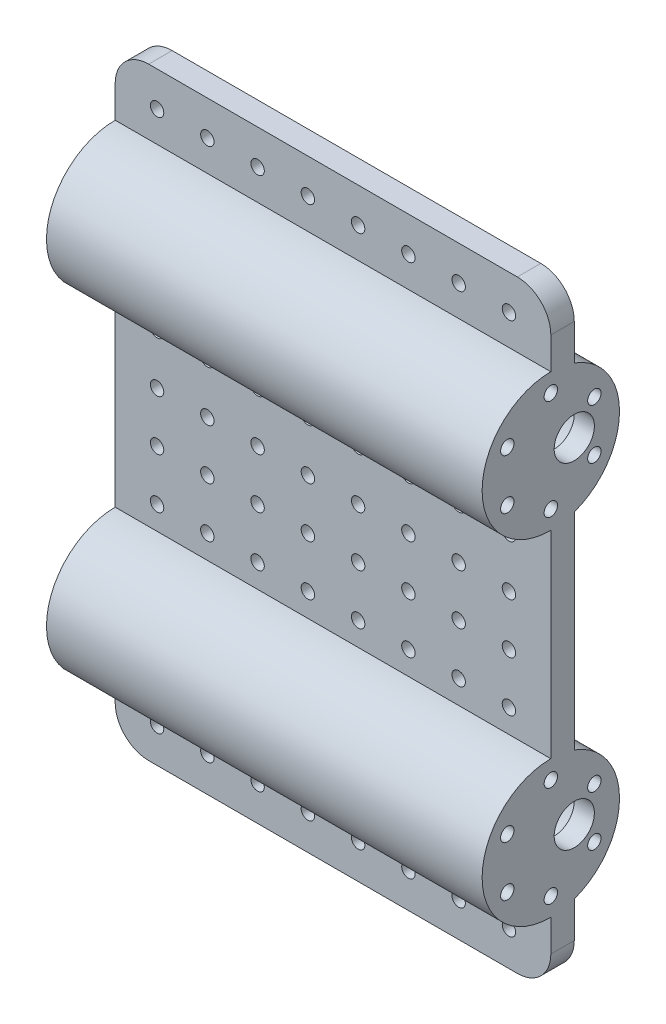
SolidWorks part; units mm, degrees
ref_plane "Ebene vorne" through (0, 0, 0) normal (0, 0, 1) x (1, 0, 0)
ref_plane "Ebene oben" through (0, 0, 0) normal (0, 1, 0) x (1, 0, 0)
ref_plane "Ebene rechts" through (0, 0, 0) normal (1, 0, 0) x (0, 0, -1)
sketch "Skizze1" plane through (0, 0, 0) normal (0, 0, 1) x (1, 0, 0)
  line L1 (0, 0) -> (130, 0)
  line L2 (0, 0) -> (0, 180)
  line L3 (0, 180) -> (130, 180)
  line L4 (130, 0) -> (130, 180)
  dimension "D1" = 130
  dimension "D2" = 180
extrude "Aufsatz-Linear austragen1" add sketch "Skizze1" along normal blind 7
sketch "Skizze2" plane through (0, 0, 0) normal (-1, 0, 0) x (0, 0, 1)
  line L0 (7, 180) -> (7, 0) construction
  line L1 (7, 180) -> (0, 180) construction
  line L3 (-37.4639, 90) -> (45.5473, 90) construction
  line L4 (0, 180) -> (0, 0) construction
  line L5 (7, 140) -> (19.9904, 147.5) construction
  line L6 (7, 140) -> (19.9904, 132.5) construction
  line L7 (-5.9904, 147.5) -> (7, 140) construction
  line L8 (7, 140) -> (-5.9904, 132.5) construction
  circle A0 centre (7, 140) radius 20.5
  circle A2 centre (0, 140) radius 6
  circle A3 centre (19.9904, 147.5) radius 2
  circle A4 centre (19.9904, 132.5) radius 2
  circle A5 centre (7, 125) radius 2
  circle A6 centre (7, 155) radius 2
  circle A7 centre (-5.9904, 147.5) radius 2
  circle A8 centre (-5.9904, 132.5) radius 2
  circle A10 centre (7, 140) radius 15 construction
  point P10 (0, 90)
  dimension "D1" = 41
  dimension "D2" = 7
  dimension "D4" = 12
  dimension "D5" = 30
  dimension "D6" = 4
  dimension "D3" = 40
  dimension "D7" = 60
  dimension "D8" = 60
  dimension "D9" = 60
  dimension "D10" = 60
ref_plane "Ebene1" through (65, 0, 0) normal (-1, 0, 0) x (0, 0, 1)
extrude "Aufsatz-Linear austragen3" add sketch "Skizze2" against normal blind 6
sketch "Skizze14" plane through (6, 0, 0) normal (1, 0, 0) x (0, 0, -1)
  circle A0 centre (-7, 140) radius 18.5
  circle A1 centre (-7, 140) radius 20.5
  arc A2 (0, 120.7322) -> (0, 159.2678) centre (-7, 140) ccw construction
  dimension "D1" = 2
extrude "Aufsatz-Linear austragen14" add sketch "Skizze14" along normal blind 10
sketch "Skizze7" plane through (6, 0, 0) normal (1, 0, 0) x (0, 0, -1)
  line L0 (0, 159.2678) -> (0, 157.1245)
  line L1 (0, 0) -> (0, 180) construction
  line L2 (0, 122.8755) -> (0, 120.7322)
  arc A0 (0, 159.2678) -> (0, 120.7322) centre (-7, 140) ccw
  arc A1 (-7, 119.5) -> (-7, 160.5) centre (-7, 140) ccw construction
  arc A2 (0, 157.1245) -> (0, 122.8755) centre (-7, 140) ccw
  dimension "D1" = 2
extrude "Aufsatz-Linear austragen4" add sketch "Skizze7" along normal up to surface (59 mm away) up to plane "Ebene1"
sketch "Skizze10" plane through (65, 0, 0) normal (-1, 0, 0) x (0, 0, 1)
  circle A0 centre (7, 140) radius 18.5
  arc A1 (7, 121.5) -> (7, 158.5) centre (7, 140) ccw construction
extrude "Schnitt-Linear austragen3" cut sketch "Skizze10" along normal up to surface (59 mm away) up to face at (6, 130.5, -5.9904)
sketch "Skizze11" plane through (0, 0, 0) normal (-1, 0, 0) x (0, 0, 1)
  line L0 (7, 157) -> (7, 153) construction
  line L1 (7, 127) -> (7, 123) construction
  circle A0 centre (7, 155) radius 2
  circle A1 centre (7, 125) radius 2
  arc A2 (7, 153) -> (7, 157) centre (7, 155) ccw construction
  arc A3 (7, 123) -> (7, 127) centre (7, 125) ccw construction
  circle A4 centre (0, 140) radius 6
  arc A5 (0, 146) -> (0, 134) centre (0, 140) ccw construction
extrude "Schnitt-Linear austragen4" cut sketch "Skizze11" against normal blind 6
mirror "Spiegeln1" about plane through (65, 0, 0) normal (-1, 0, 0) of "Aufsatz-Linear austragen14", "Aufsatz-Linear austragen3", "Aufsatz-Linear austragen4", "Schnitt-Linear austragen3", "Schnitt-Linear austragen4"
ref_plane "Ebene2" through (0, 90, 0) normal (0, -1, 0) x (-1, 0, 0)
mirror "Spiegeln2" about plane through (0, 90, 0) normal (0, -1, 0) of "Spiegeln1", "Schnitt-Linear austragen4", "Schnitt-Linear austragen3", "Aufsatz-Linear austragen4", "Aufsatz-Linear austragen3"
sketch "Skizze13" plane through (0, 0, 0) normal (0, 0, -1) x (-1, 0, 0)
  line L0 (-130, 140) -> (0, 140) construction
  line L5 (-130, 159.2678) -> (-130, 120.7322) construction
  line L6 (0, 120.7322) -> (0, 159.2678) construction
  line L7 (0, 120.7322) -> (0, 59.2678) construction
  line L8 (-130, 159.2678) -> (-130, 180) construction
  line L9 (0, 180) -> (0, 159.2678) construction
  line L10 (0, 90) -> (-130, 90) construction
  line L11 (-130, 59.2678) -> (-130, 120.7322) construction
  circle A24 centre (-12.5, 112.5) radius 2
  circle A25 centre (-27.5, 112.5) radius 2
  circle A26 centre (-42.5, 112.5) radius 2
  circle A27 centre (-57.5, 112.5) radius 2
  circle A28 centre (-72.5, 112.5) radius 2
  circle A29 centre (-87.5, 112.5) radius 2
  circle A30 centre (-102.5, 112.5) radius 2
  circle A31 centre (-117.5, 112.5) radius 2
  circle A32 centre (-27.5, 97.5) radius 2
  circle A33 centre (-42.5, 97.5) radius 2
  circle A34 centre (-57.5, 97.5) radius 2
  circle A35 centre (-72.5, 97.5) radius 2
  circle A36 centre (-87.5, 97.5) radius 2
  circle A37 centre (-102.5, 97.5) radius 2
  circle A38 centre (-117.5, 97.5) radius 2
  circle A39 centre (-27.5, 82.5) radius 2
  circle A40 centre (-42.5, 82.5) radius 2
  circle A41 centre (-57.5, 82.5) radius 2
  circle A42 centre (-72.5, 82.5) radius 2
  circle A43 centre (-87.5, 82.5) radius 2
  circle A44 centre (-102.5, 82.5) radius 2
  circle A45 centre (-117.5, 82.5) radius 2
  circle A46 centre (-27.5, 67.5) radius 2
  circle A47 centre (-42.5, 67.5) radius 2
  circle A48 centre (-57.5, 67.5) radius 2
  circle A49 centre (-72.5, 67.5) radius 2
  circle A50 centre (-87.5, 67.5) radius 2
  circle A51 centre (-102.5, 67.5) radius 2
  circle A52 centre (-117.5, 67.5) radius 2
  circle A53 centre (-12.5, 97.5) radius 2
  circle A54 centre (-12.5, 82.5) radius 2
  circle A55 centre (-12.5, 67.5) radius 2
  circle A56 centre (-117.5, 169.6339) radius 2
  circle A57 centre (-102.5, 169.6339) radius 2
  circle A58 centre (-87.5, 169.6339) radius 2
  circle A59 centre (-72.5, 169.6339) radius 2
  circle A60 centre (-57.5, 169.6339) radius 2
  circle A61 centre (-42.5, 169.6339) radius 2
  circle A62 centre (-27.5, 169.6339) radius 2
  circle A63 centre (-12.5, 169.6339) radius 2
  circle A64 centre (-12.5, 10.3661) radius 2
  circle A65 centre (-27.5, 10.3661) radius 2
  circle A66 centre (-42.5, 10.3661) radius 2
  circle A67 centre (-57.5, 10.3661) radius 2
  circle A68 centre (-72.5, 10.3661) radius 2
  circle A69 centre (-87.5, 10.3661) radius 2
  circle A70 centre (-102.5, 10.3661) radius 2
  circle A71 centre (-117.5, 10.3661) radius 2
  point P97 (0, 169.6339)
  dimension "D3" = 8
  dimension "D1" = 4
  dimension "D7" = 4
  dimension "D2" = 12.5
  dimension "D6" = 15
  dimension "D4" = 4
  dimension "D5" = 15
  dimension "D8" = 12.5
  dimension "D10" = 15
  dimension "D9" = 8
extrude "Schnitt-Linear austragen6" cut sketch "Skizze13" against normal blind 20
fillet "Verrundung1" radius 10 4 edges at (0, 180, 3.5) (130, 180, 3.5) (130, 0, 3.5) (0, 0, 3.5)
sketch "Skizze15" plane through (0, 0, 0) normal (-1, 0, 0) x (0, 0, 1)
  line L0 (27.65, 140) -> (27.65, 40)
  line L1 (27.65, 140) -> (27.5, 140) construction
  line L2 (27.65, 40) -> (27.5, 40) construction
  line L3 (7.15, 119.3505) -> (7.15, 60.6495)
  line L4 (7, 119.5) -> (7, 60.5) construction
  arc A0 (27.65, 40) -> (7.15, 60.6495) centre (7, 40) ccw
  arc A2 (7, 119.5) -> (7, 160.5) centre (7, 140) ccw construction
  arc A3 (7, 19.5) -> (7, 60.5) centre (7, 40) ccw construction
  arc A4 (7.15, 119.3505) -> (27.65, 140) centre (7, 140) ccw
  dimension "D1" = 0.15
  dimension "D2" = 0.15
  dimension "D3" = 0.15
extrude "Aufsatz-Linear austragen15" [suppressed] add sketch "Skizze15" against normal up to surface (130 mm away) separate body
sketch "Skizze16" [suppressed] plane through (0, 0, 7.15) normal (0, 0, -1) x (-1, 0, 0)
  line L0 (-130, 119.3505) -> (0, 119.3505) construction
  line L1 (-127, 63.6495) -> (-3, 63.6495)
  line L2 (-127, 63.6495) -> (-127, 116.3505)
  line L3 (-127, 116.3505) -> (-3, 116.3505)
  line L4 (-3, 63.6495) -> (-3, 116.3505)
  line L6 (-130, 60.6495) -> (0, 60.6495) construction
  line L7 (0, 119.3505) -> (0, 60.6495) construction
  line L8 (-130, 60.6495) -> (-130, 119.3505) construction
  dimension "D1" = 3
  dimension "D2" = 3
  dimension "D3" = 3
  dimension "D4" = 3
extrude "Schnitt-Linear austragen7" [suppressed] cut sketch "Skizze16" against normal offset from surface (17.5 mm away) 3
sketch "Skizze17" [suppressed] plane through (0, 0, 7.15) normal (0, 0, -1) x (-1, 0, 0)
  line L0 (-127, 90) -> (-3, 90) construction
  line L1 (-3, 63.6495) -> (-18, 63.6495)
  line L2 (-3, 63.6495) -> (-3, 71.6495)
  line L3 (-3, 71.6495) -> (-18, 71.6495)
  line L4 (-18, 63.6495) -> (-18, 71.6495)
  line L5 (-127, 116.3505) -> (-127, 63.6495) construction
  line L6 (-3, 63.6495) -> (-3, 116.3505) construction
  line L7 (-65, 116.3505) -> (-65, 63.6495) construction
  line L8 (-3, 116.3505) -> (-127, 116.3505) construction
  line L9 (-127, 63.6495) -> (-3, 63.6495) construction
  line L10 (-18, 116.3505) -> (-18, 108.3505)
  line L11 (-3, 108.3505) -> (-18, 108.3505)
  line L12 (-3, 116.3505) -> (-3, 108.3505)
  line L13 (-3, 116.3505) -> (-18, 116.3505)
  line L14 (-127, 116.3505) -> (-112, 116.3505)
  line L15 (-127, 116.3505) -> (-127, 108.3505)
  line L16 (-127, 108.3505) -> (-112, 108.3505)
  line L17 (-112, 116.3505) -> (-112, 108.3505)
  line L18 (-112, 63.6495) -> (-112, 71.6495)
  line L19 (-127, 71.6495) -> (-112, 71.6495)
  line L20 (-127, 63.6495) -> (-127, 71.6495)
  line L21 (-127, 63.6495) -> (-112, 63.6495)
  circle A0 centre (-117.5, 112.5) radius 2
  circle A1 centre (-117.5, 112.5) radius 2 construction
  circle A2 centre (-117.5, 67.5) radius 2
  circle A3 centre (-12.5, 67.5) radius 2
  circle A4 centre (-12.5, 112.5) radius 2
  dimension "D1" = 8
  dimension "D2" = 15
extrude "Aufsatz-Linear austragen16" [suppressed] add sketch "Skizze17" against normal blind 4
sketch "Skizze18" [suppressed] plane through (0, 0, 0) normal (0, 0, -1) x (-1, 0, 0)
  line L0 (-130, 159.2678) -> (-130, 170) construction
  line L1 (-110, 203.1952) -> (41.3252, 203.1952)
  line L2 (-110, 203.1952) -> (-110, -31.3619)
  line L3 (-110, -31.3619) -> (41.3252, -31.3619)
  line L4 (41.3252, 203.1952) -> (41.3252, -31.3619)
  dimension "D1" = 20
extrude "Schnitt-Linear austragen8" [suppressed] cut sketch "Skizze18" against normal through all both and the other way through all
sketch "Skizze19" [suppressed] plane through (110, 0, 0) normal (-1, 0, 0) x (0, 0, 1)
  line L0 (7, 19.5) -> (7, 0) construction
  line L1 (7, 0) -> (19.5, 0)
  line L2 (7, 0) -> (7, 19.5)
  line L4 (19.5, 0) -> (19.5, 23.7519)
  arc A0 (7, 19.5) -> (7, 60.5) centre (7, 40) ccw construction
  arc A1 (7, 19.5) -> (19.5, 23.7519) centre (7, 40) ccw
  circle A2 centre (14.5, 15) radius 2
  circle A3 centre (14.5, 7) radius 2
  dimension "D2" = 4
  dimension "D3" = 4
  dimension "D1" = 12.5
  dimension "D4" = 8
  dimension "D5" = 7
  dimension "D6" = 5
extrude "Aufsatz-Linear austragen17" [suppressed] add sketch "Skizze19" against normal blind 4.5
sketch "Skizze20" [suppressed] plane through (0, 0, 0) normal (0, 0, -1) x (-1, 0, 0)
  circle A0 centre (-117.5, 10.3661) radius 2
  circle A1 centre (-117.5, 10.3661) radius 2 construction
extrude "Aufsatz-Linear austragen18" [suppressed] add sketch "Skizze20" against normal up to surface (7 mm away)
mirror "Spiegeln3" [suppressed] about plane through (0, 90, 0) normal (0, -1, 0)
sketch "Skizze22" [suppressed] plane through (0, 0, 0) normal (0, 0, -1) x (-1, 0, 0)
  line L0 (-130, 59.2678) -> (-130, 120.7322) construction
  line L1 (-184.0519, 199.1472) -> (-110, 199.1472)
  line L2 (-184.0519, 199.1472) -> (-184.0519, -18.2596)
  line L3 (-184.0519, -18.2596) -> (-110, -18.2596)
  line L4 (-110, 199.1472) -> (-110, -18.2596)
  line L5 (-20, 195.6559) -> (82.6594, 195.6559)
  line L6 (-20, 195.6559) -> (-20, -42.2615)
  line L7 (-20, -42.2615) -> (82.6594, -42.2615)
  line L8 (82.6594, 195.6559) -> (82.6594, -42.2615)
  line L9 (0, 120.7322) -> (0, 59.2678) construction
  dimension "D1" = 20
  dimension "D2" = 20
extrude "Schnitt-Linear austragen9" [suppressed] cut sketch "Skizze22" against normal through all both and the other way through all
sketch "Skizze23" [suppressed] plane through (20, 0, 0) normal (-1, 0, 0) x (0, 0, 1)
  line L1 (7, 0) -> (19.5, 0)
  line L2 (7, 0) -> (7, 19.5)
  line L4 (19.5, 0) -> (19.5, 23.7519)
  arc A0 (7, 19.5) -> (19.5, 23.7519) centre (7, 40) ccw
  arc A1 (7, 19.5) -> (7, 60.5) centre (7, 40) ccw construction
  circle A2 centre (14.5, 7) radius 2
  circle A3 centre (14.5, 15) radius 2
  dimension "D2" = 4
  dimension "D3" = 4
  dimension "D1" = 12.5
  dimension "D4" = 7
  dimension "D5" = 8
  dimension "D6" = 5
extrude "Aufsatz-Linear austragen19" [suppressed] add sketch "Skizze23" against normal blind 4.5
mirror "Spiegeln4" [suppressed] about plane through (65, 0, 0) normal (-1, 0, 0)
mirror "Spiegeln5" [suppressed] about plane through (0, 90, 0) normal (0, -1, 0)
